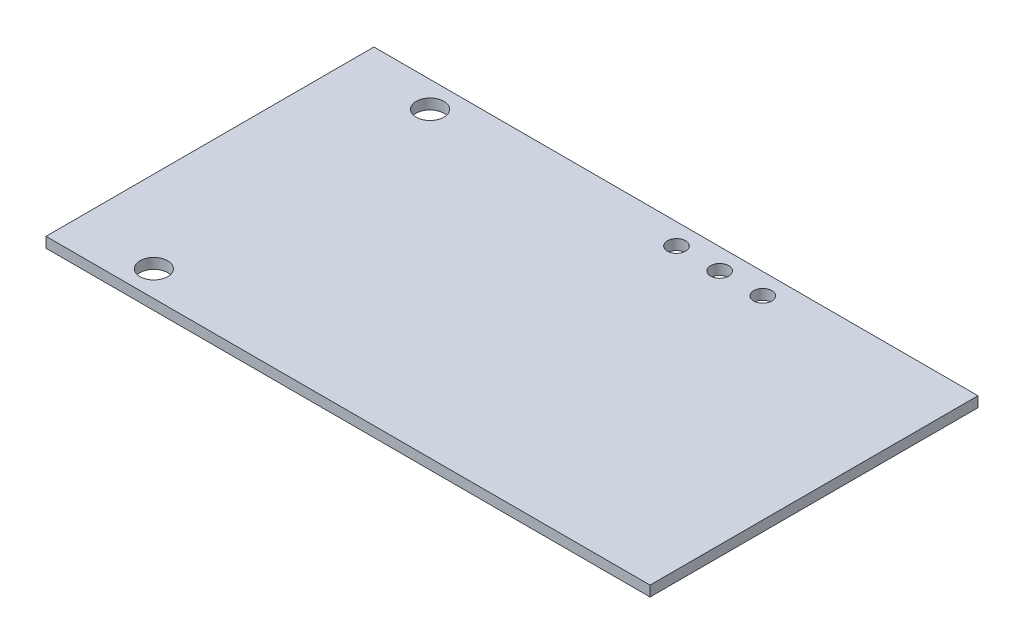
SolidWorks part; units mm, degrees
ref_plane "Front Plane" through (0, 0, 0) normal (0, 0, 1) x (1, 0, 0)
ref_plane "Top Plane" through (0, 0, 0) normal (0, 1, 0) x (1, 0, 0)
ref_plane "Right Plane" through (0, 0, 0) normal (1, 0, 0) x (0, 0, -1)
sketch "Sketch1" plane through (0, 0, 0) normal (0, 1, 0) x (1, 0, 0)
  line L1 (35, -19) -> (-35, -19)
  line L2 (35, -19) -> (35, 19)
  line L3 (35, 19) -> (-35, 19)
  line L4 (-35, -19) -> (-35, 19)
  line L5 (35, -19) -> (-35, 19) construction
  line L6 (35, 19) -> (-35, -19) construction
  point P0 (0, 0)
  dimension "D1" = 70
  dimension "D2" = 38
extrude "Boss-Extrude1" add sketch "Sketch1" along normal blind 1.2
sketch "Sketch2" plane through (0, 1.2, 0) normal (0, 1, 0) x (1, 0, 0)
  line L0 (-35, 19) -> (-35, -19) construction
  line L1 (-35, -19) -> (35, -19) construction
  circle A0 centre (-25.5, 16) radius 1.6
  circle A1 centre (-25.5, -16) radius 1.6
  circle A2 centre (2.5, 16.56) radius 1.05
  circle A3 centre (7.5, 16.56) radius 1.05
  circle A4 centre (12.5, 16.56) radius 1.05
  dimension "D1" = 3.2
  dimension "D5" = 2.1
  dimension "D2" = 9.5
  dimension "D3" = 3
  dimension "D4" = 35
  dimension "D6" = 37.5
  dimension "D7" = 42.5
  dimension "D8" = 47.5
  dimension "D9" = 35.56
extrude "Cut-Extrude1" cut sketch "Sketch2" against normal through all
